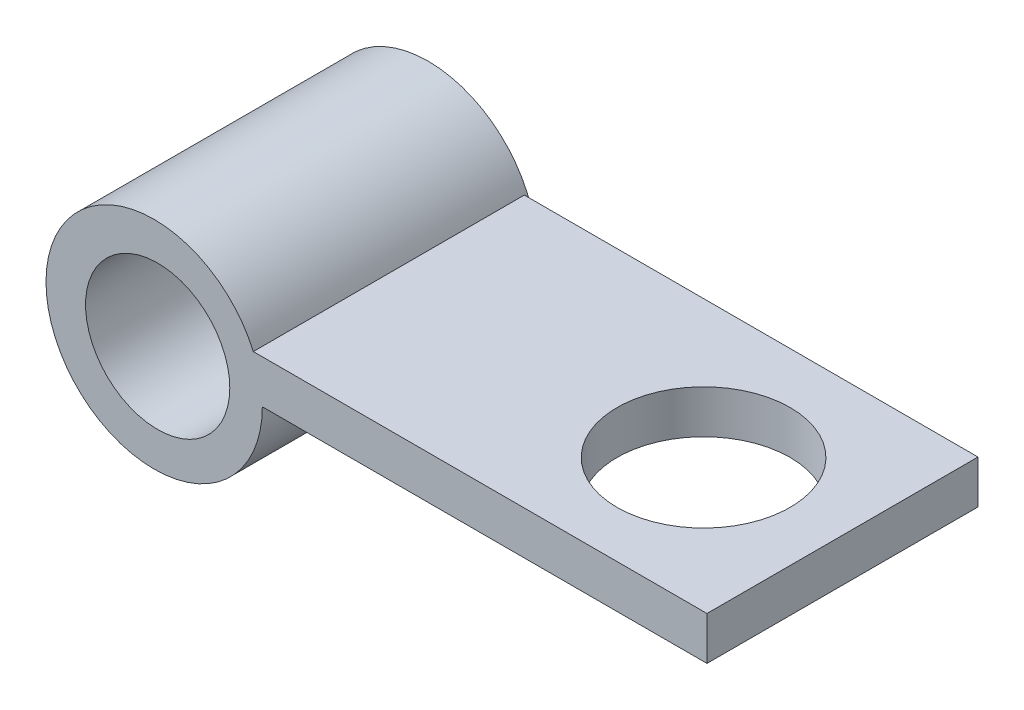
SolidWorks part; units mm, degrees
ref_plane "Ön Düzlem" through (0, 0, 0) normal (0, 0, 1) x (1, 0, 0)
ref_plane "Üst Düzlem" through (0, 0, 0) normal (0, 1, 0) x (1, 0, 0)
ref_plane "Sağ Düzlem" through (0, 0, 0) normal (1, 0, 0) x (0, 0, -1)
sketch3d "3DSketch1"
  line L1 (-1.907, 0, 4.7539) -> (-1.907, 0, 23.5452)
  line L2 (-1.907, 0, 4.7539) -> (29.5604, 0, 4.7539)
  line L3 (29.5604, 0, 4.7539) -> (29.5604, 0, 23.5452)
  line L4 (-1.907, 0, 23.5452) -> (29.5604, 0, 23.5452)
  line L5 (-1.907, 0, 4.7539) -> (29.5604, 0, 23.5452) construction
  line L6 (29.5604, 0, 4.7539) -> (-1.907, 0, 23.5452) construction
  circle A0 centre (20.0738, 0, 14.2931) radius 6
  point P4 (11.0326, 1.9055, 15.2535)
  point P5 (13.8267, 0, 14.1495)
  point P8 (20.0738, 6, 14.2931)
  dimension "D2" = 18.7913
  dimension "D3" = 12
  dimension "D1" = 31.4674
extrude "Boss-Extrude3" add sketch "3DSketch1" along direction (0, 1, 0) on the side against the normal blind 3 separate body
sketch "Sketch3" plane through (-8.5257, 0, 23.5452) normal (0, 0, 1) x (1, 0, 0)
  circle A0 centre (0, 0) radius 5
  circle A1 centre (-0.2429, 0) radius 7.5
  dimension "D1" = 10
  dimension "D2" = 15
extrude "Boss-Extrude5" add sketch "Sketch3" against normal blind 19
